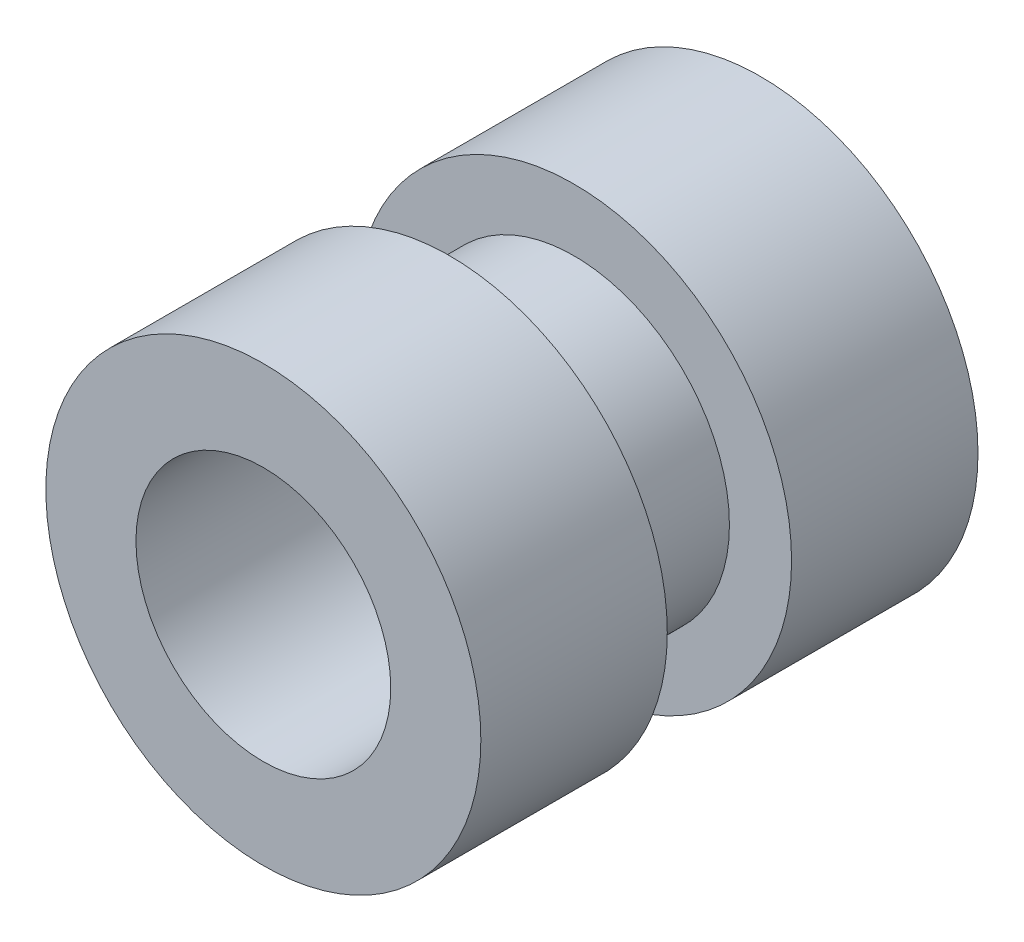
SolidWorks part; units mm, degrees
material "H62"
ref_plane "前视基准面" through (0, 0, 0) normal (0, 0, 1) x (1, 0, 0)
ref_plane "上视基准面" through (0, 0, 0) normal (0, 1, 0) x (1, 0, 0)
ref_plane "右视基准面" through (0, 0, 0) normal (1, 0, 0) x (0, 0, -1)
other "Configuration Table"
sketch "草图1" plane through (0, 0, 0) normal (0, 0, 1) x (1, 0, 0)
  circle A0 centre (0, 0) radius 1.75
  dimension "D1" = 3.5
extrude "凸台-拉伸1" add sketch "草图1" along normal blind 1.5
sketch "草图2" plane through (0, 0, 1.5) normal (0, 0, 1) x (1, 0, 0)
  circle A0 centre (0, 0) radius 1.25
  circle A1 centre (0, 0) radius 1.75 construction
  dimension "D1" = 0.5
extrude "凸台-拉伸2" add sketch "草图2" along normal blind 1
sketch "草图3" plane through (0, 0, 2.5) normal (0, 0, 1) x (1, 0, 0)
  circle A1 centre (0, 0) radius 1.75
  circle A2 centre (0, 0) radius 1.75
  dimension "D1" = 0
extrude "凸台-拉伸3" add sketch "草图3" along normal blind 1.5
hole_wizard "M2.5 螺纹孔1" positions "草图4" profile "草图5" tap size "M2.5" standard "GB" end condition through all
sketch "草图4" plane through (0, 0, 4) normal (0, 0, 1) x (1, 0, 0)
  point P0 (0, 0)
sketch "草图5" plane through (0, 0, 4) normal (1, 0, 0) x (0, -1, 0)
  line L0 (0, 0) -> (0, 4)
  line L1 (0, 4) -> (1.025, 4)
  line L2 (1.025, 4) -> (1.025, 0)
  line L5 (1.025, 0) -> (0, 0)
  line L11 (0, -6.35) -> (0, 107.95) construction
  dimension "通孔螺纹孔钻头直径" = 2.05
  dimension "通孔螺纹孔钻头深度" = 4
cosmetic thread "孔螺蚊线1" parameters "D2"=2.5
